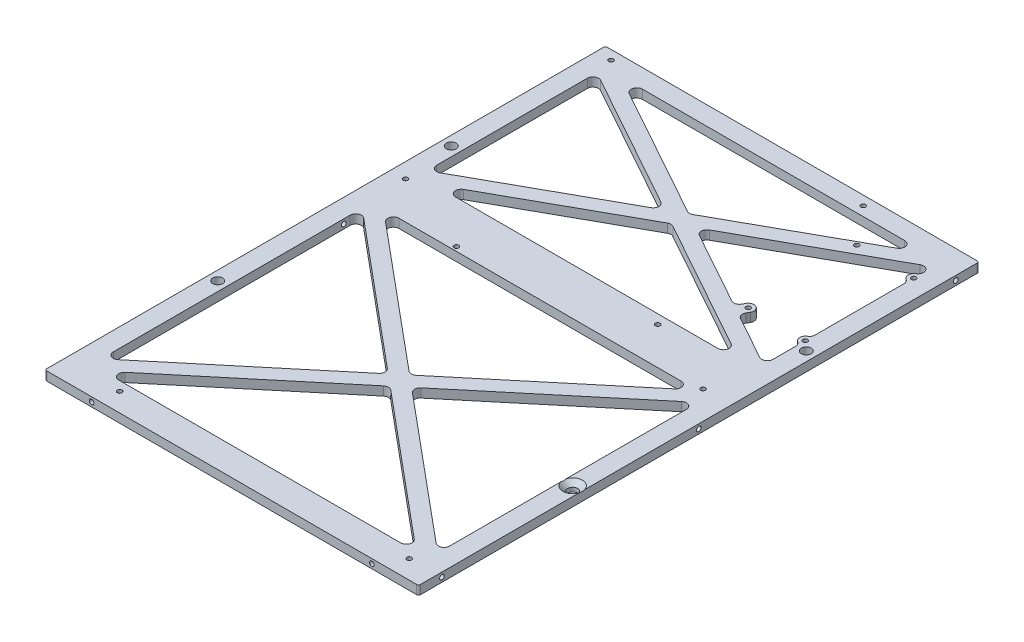
SolidWorks part; units mm, degrees
material "6061 Alloy"
ref_plane "Front Plane" through (0, 0, 0) normal (0, 0, 1) x (1, 0, 0)
ref_plane "Top Plane" through (0, 0, 0) normal (0, 1, 0) x (1, 0, 0)
ref_plane "Right Plane" through (0, 0, 0) normal (1, 0, 0) x (0, 0, -1)
sketch "Sketch1" plane through (0, 0, 0) normal (0, 1, 0) x (1, 0, 0)
  line L1 (-100, -150) -> (100, -150)
  line L2 (-100, -150) -> (-100, 150)
  line L3 (-100, 150) -> (100, 150)
  line L4 (100, -150) -> (100, 150)
  line L5 (-100, -150) -> (100, 150) construction
  line L6 (-100, 150) -> (100, -150) construction
  point P0 (0, 0)
  dimension "D1" = 300
  dimension "D2" = 200
extrude "Boss-Extrude1" add sketch "Sketch1" along normal blind 4.7625
sketch "Sketch10" plane through (0, 4.7625, 0) normal (0, 1, 0) x (1, 0, 0)
  line L0 (-100, -150) -> (100, -150) construction
  line L1 (-70, -140) -> (85, -140) construction
  line L2 (-70, -140) -> (-70, 17.25) construction
  line L3 (-70, 17.25) -> (85, 17.25) construction
  line L4 (85, -140) -> (85, 17.25) construction
  line L5 (-70, -140) -> (85, 17.25) construction
  line L6 (-70, 17.25) -> (85, -140) construction
  line L7 (100, 150) -> (-100, 150) construction
  line L8 (-92, 35) -> (43, 35) construction
  line L14 (-92, 35) -> (-92, 145) construction
  line L15 (100, -150) -> (100, 150) construction
  line L16 (-92, 145) -> (43, 145) construction
  line L17 (-95, -62.5) -> (95, -62.5) construction
  line L18 (-95, -62.5) -> (-95, 62.5) construction
  line L19 (-95, 62.5) -> (95, 62.5) construction
  line L20 (95, -62.5) -> (95, 62.5) construction
  line L21 (-95, -62.5) -> (95, 62.5) construction
  line L22 (-95, 62.5) -> (95, -62.5) construction
  line L23 (43, 35) -> (43, 145) construction
  line L24 (-92, 35) -> (43, 145) construction
  line L25 (-92, 145) -> (43, 35) construction
  line L26 (-100, 150) -> (-100, -150) construction
  line L28 (59.5, 67) -> (90, 67) construction
  line L29 (59.5, 67) -> (59.5, 125) construction
  line L30 (59.5, 125) -> (90, 125) construction
  line L31 (90, 67) -> (90, 125) construction
  line L32 (59.5, 67) -> (90, 125) construction
  line L33 (59.5, 125) -> (90, 67) construction
  point P0 (7.5, -61.375)
  point P7 (-47, 17.25)
  point P9 (-24.5, 90)
  point P14 (74.75, 96)
  point P20 (0, 0)
  dimension "D1" = 155
  dimension "D2" = 157.25
  dimension "D3" = 132
  dimension "D4" = 10
  dimension "D5" = 135
  dimension "D6" = 125
  dimension "D7" = 110
  dimension "D8" = 5
  dimension "D9" = 8
  dimension "D10" = 190
  dimension "D11" = 15
  dimension "D12" = 30.5
  dimension "D13" = 58
  dimension "D14" = 25
  dimension "D15" = 10
sketch "Sketch14" plane through (0, 4.7625, 0) normal (0, 1, 0) x (1, 0, 0)
  line L0 (100, 150) -> (-100, 150) construction
  line L1 (-90, 40) -> (90, 40) construction
  line L2 (-90, 40) -> (-90, 140) construction
  line L3 (-90, 140) -> (90, 140) construction
  line L4 (90, 40) -> (90, 140) construction
  line L5 (-90, 40) -> (90, 140) construction
  line L6 (-90, 140) -> (90, 40) construction
  line L7 (-90, 15) -> (90, 15) construction
  line L8 (-90, 15) -> (-90, -135) construction
  line L9 (-90, -135) -> (90, -135) construction
  line L10 (90, 15) -> (90, -135) construction
  line L11 (-90, 15) -> (90, -135) construction
  line L12 (-90, -135) -> (90, 15) construction
  line L13 (-100, 150) -> (-100, -150) construction
  line L14 (-100, -150) -> (100, -150) construction
  line L15 (-92.5607, 11.9271) -> (87.4393, -138.0729) construction
  line L16 (-87.4393, -138.0729) -> (92.5607, 11.9271) construction
  line L17 (-88.0574, 36.5034) -> (91.9426, 136.5034) construction
  line L18 (-91.9426, 136.5034) -> (88.0574, 36.5034) construction
  line L19 (-87.4393, 18.0729) -> (92.5607, -131.9271) construction
  line L20 (-92.5607, -131.9271) -> (87.4393, 18.0729) construction
  line L21 (-91.9426, 43.4966) -> (88.0574, 143.4966) construction
  line L22 (-88.0574, 143.4966) -> (91.9426, 43.4966) construction
  line L23 (-83.7518, 15) -> (83.7518, 15)
  line L24 (90, 9.7932) -> (90, -129.7932)
  line L25 (83.7518, -135) -> (-83.7518, -135)
  line L26 (-90, -129.7932) -> (-90, 9.7932)
  line L27 (83.7518, 15) -> (0, -54.7932)
  line L28 (0, -54.7932) -> (-83.7518, 15)
  line L29 (-90, 9.7932) -> (-6.2482, -60)
  line L30 (-6.2482, -60) -> (-90, -129.7932)
  line L31 (-83.7518, -135) -> (0, -65.2068)
  line L32 (0, -65.2068) -> (83.7518, -135)
  line L33 (90, -129.7932) -> (6.2482, -60)
  line L34 (6.2482, -60) -> (90, 9.7932)
  line L35 (8.2365, 90) -> (90, 135.4242)
  line L36 (90, 135.4242) -> (90, 44.5758) construction
  line L37 (90, 44.5758) -> (8.2365, 90) construction
  line L38 (81.7635, 140) -> (0, 94.5758)
  line L39 (0, 94.5758) -> (-81.7635, 140)
  line L40 (-81.7635, 140) -> (81.7635, 140)
  line L41 (-90, 135.4242) -> (-8.2365, 90)
  line L42 (-8.2365, 90) -> (-90, 44.5758)
  line L43 (-90, 44.5758) -> (-90, 135.4242)
  line L44 (-81.7635, 40) -> (0, 85.4242)
  line L45 (0, 85.4242) -> (81.7635, 40)
  line L46 (81.7635, 40) -> (-81.7635, 40)
  line L47 (54.5512, 64.2696) -> (56.8775, 68.4569)
  line L48 (62.1225, 65.5431) -> (59.7962, 61.3557)
  line L49 (59.7962, 61.3557) -> (90, 44.5758)
  line L50 (54.5512, 64.2696) -> (8.2365, 90)
  line L51 (90, 64) -> (90, 44.5758)
  line L52 (90, 70) -> (90, 122)
  line L53 (90, 128) -> (90, 135.4242)
  circle A0 centre (90, 125) radius 3 construction
  circle A1 centre (90, 67) radius 3 construction
  circle A2 centre (59.5, 67) radius 3 construction
  arc A3 (56.8775, 68.4569) -> (62.1225, 65.5431) centre (59.5, 67) cw
  arc A4 (90, 70) -> (90, 64) centre (90, 67) ccw
  arc A5 (90, 128) -> (90, 122) centre (90, 125) ccw
  point P0 (0, 90)
  point P5 (0, -60)
  dimension "D9" = 3
  dimension "D10" = 6
  dimension "D11" = 6
  dimension "D1" = 10
  dimension "D2" = 100
  dimension "D3" = 10
  dimension "D4" = 15
  dimension "D5" = 150
  dimension "D6" = 10
  dimension "D7" = 4
  dimension "D8" = 4
extrude "Cut-Extrude1" cut sketch "Sketch14" against normal through all
sketch "Sketch15" plane through (0, 4.7625, 0) normal (0, 1, 0) x (1, 0, 0)
  circle A0 centre (85, -140) radius 3.5
  dimension "D1" = 7
extrude "Boss-Extrude2" add sketch "Sketch15" against normal up to surface (4.7625 mm away) up to face at (70.6401, 0, -83.2953)
hole_wizard "M3x0.5 Tapped Hole3" positions "Sketch11" profile "Sketch12" tap size "M3x0.5" standard "ANSI Metric" end condition through all
sketch "Sketch11" plane through (0, 4.7625, 0) normal (0, 1, 0) x (1, 0, 0)
  point P3 (85, 17.25)
  point P6 (-47, 17.25)
  point P9 (85, -140)
  point P33 (-70, -140)
  point P42 (-92, 145)
  point P45 (-92, 35)
  point P48 (43, 35)
  point P51 (43, 145)
  point P54 (59.5, 67)
  point P57 (90, 67)
  point P60 (90, 125)
  point P63 (59.5, 125)
sketch "Sketch12" plane through (85, 4.7625, -17.25) normal (1, 0, 0) x (0, 0, 1)
  line L0 (0, 0) -> (0, 4.7625)
  line L1 (0, 4.7625) -> (1.25, 4.7625)
  line L2 (1.25, 4.7625) -> (1.25, 0)
  line L5 (1.25, 0) -> (0, 0)
  line L11 (0, -6.35) -> (0, 107.95) construction
  dimension "Thru Tap Drill Dia." = 2.5
  dimension "Thru Tap Drill Depth" = 4.7625
cosmetic thread "Hole Thread7" parameters "D2"=3
cosmetic thread "Hole Thread9" parameters "D2"=3
cosmetic thread "Hole Thread32" parameters "D2"=3
cosmetic thread "Hole Thread33" parameters "D2"=3
cosmetic thread "Hole Thread38" parameters "D2"=3
cosmetic thread "Hole Thread39" parameters "D2"=3
cosmetic thread "Hole Thread40" parameters "D2"=3
cosmetic thread "Hole Thread41" parameters "D2"=3
cosmetic thread "Hole Thread42" parameters "D2"=3
cosmetic thread "Hole Thread43" parameters "D2"=3
cosmetic thread "Hole Thread44" parameters "D2"=3
cosmetic thread "Hole Thread45" parameters "D2"=3
hole_wizard "M5 Clearance Hole1" positions "Sketch26" profile "Sketch27" hole size "M5" standard "ANSI Metric" end condition through all
sketch "Sketch26" plane through (0, 4.7625, 0) normal (0, 1, 0) x (1, 0, 0)
  point P0 (-95, 62.5)
  point P3 (-95, -62.5)
  point P6 (95, -62.5)
  point P9 (95, 62.5)
sketch "Sketch27" plane through (-95, 4.7625, -62.5) normal (1, 0, 0) x (0, 0, 1)
  line L0 (0, 0) -> (0, 4.7625)
  line L1 (0, 4.7625) -> (2.65, 4.7625)
  line L2 (2.65, 4.7625) -> (2.65, 0)
  line L5 (2.65, 0) -> (0, 0)
  line L11 (0, -6.35) -> (0, 107.95) construction
  dimension "Thru Hole Dia." = 5.3
  dimension "Thru Hole Depth" = 4.7625
hole_wizard "CSK for M5 Flat Head Machine Screw1" positions "Sketch28" profile "Sketch29" countersink size "M5" standard "ANSI Metric" end condition through all
sketch "Sketch28" plane through (0, 4.7625, 0) normal (0, 1, 0) x (1, 0, 0)
  point P0 (95, -62.5)
sketch "Sketch29" plane through (95, 4.7625, 62.5) normal (1, 0, 0) x (0, 0, 1)
  line L0 (0, 0) -> (0, 4.7625)
  line L1 (0, 4.7625) -> (2.65, 4.7625)
  line L2 (2.65, 4.7625) -> (2.65, 2.55)
  line L3 (2.65, 2.55) -> (5.2, 0)
  line L5 (5.2, 0) -> (0, 0)
  line L6 (-2.65, 2.55) -> (-5.2, 0) construction
  line L11 (0, -6.35) -> (0, 107.95) construction
  dimension "Thru Hole Dia." = 5.3
  dimension "Thru Hole Depth" = 4.7625
  dimension "Near C'Sink Dia." = 10.4
  dimension "Near C'Sink Angle" = 90
fillet "Fillet2" radius 3 30 edges at (81.7635, 2.3813, -140) (-81.7635, 2.3813, -140) (0, 2.3813, -94.5758) (0, 2.3813, -85.4242) (81.7635, 2.3813, -40) (-81.7635, 2.3813, -40) (-90, 2.3813, -135.4242) (-8.2365, 2.3813, -90) (-90, 2.3813, -44.5758) (90, 2.3813, -9.7932) (90, 2.3813, 129.7932) (83.7518, 2.3813, 135) (-83.7518, 2.3813, 135) (-90, 2.3813, 129.7932) (-6.2482, 2.3813, 60) (6.2482, 2.3813, 60) (0, 2.3813, 65.2068) (-90, 2.3813, -9.7932) (83.7518, 2.3813, -15) (0, 2.3813, 54.7932) (-83.7518, 2.3813, -15) (90, 2.3813, -135.4242) (90, 2.3813, -128) (90, 2.3813, -122) (90, 2.3813, -70) (90, 2.3813, -64) (90, 2.3813, -44.5758) (59.7962, 2.3813, -61.3557) (54.5512, 2.3813, -64.2696) (8.2365, 2.3813, -90)
sketch "Sketch17" plane through (0, 0, 150) normal (0, 0, 1) x (1, 0, 0)
  line L0 (-75, 2.3813) -> (75, 2.3813) construction
  line L1 (-100, 4.7625) -> (-100, 0) construction
  point P3 (0, 2.3813)
  point P7 (-100, 2.3813)
  dimension "D1" = 150
hole_wizard "M3x0.5 Tapped Hole4" positions "Sketch20" profile "Sketch22" tap size "M3x0.5" standard "ANSI Metric"
sketch "Sketch20" plane through (0, 0, 150) normal (0, 0, 1) x (1, 0, 0)
  point P0 (-75, 2.3813)
  point P3 (75, 2.3813)
sketch "Sketch22" plane through (-75, 2.3813, 150) normal (1, 0, 0) x (0, -1, 0)
  line L0 (0, 0) -> (0, 10.7511)
  line L1 (0, 10.7511) -> (1.25, 10)
  line L2 (1.25, 10) -> (1.25, 0)
  line L5 (1.25, 0) -> (0, 0)
  line L10 (0, 10.7511) -> (-1.25, 10) construction
  line L11 (0, -6.35) -> (0, 107.95) construction
  dimension "Tap Drill Dia." = 2.5
  dimension "Tap Drill Depth" = 10
  dimension "Drill Angle" = 118
cosmetic thread "Hole Thread22" parameters "D1"=4.76, "D2"=3
cosmetic thread "Hole Thread23" parameters "D1"=4.76, "D2"=3
mirror "Mirror1" about plane through (0, 0, 0) normal (0, 0, 1) of "M3x0.5 Tapped Hole4"
cosmetic thread "Hole Thread28" parameters "D1"=4.76, "D2"=3
cosmetic thread "Hole Thread29" parameters "D1"=4.76, "D2"=3
sketch "Sketch23" plane through (-100, 0, 0) normal (-1, 0, 0) x (0, 0, 1)
  line L0 (-137.5, 2.3813) -> (137.5, 2.3813) construction
  line L1 (-150, 4.7625) -> (-150, 0) construction
  point P3 (0, 2.3813)
  point P6 (-150, 2.3813)
  dimension "D1" = 275
hole_wizard "M3x0.5 Tapped Hole5" positions "Sketch24" profile "Sketch25" tap size "M3x0.5" standard "ANSI Metric"
sketch "Sketch24" plane through (-100, 0, 0) normal (-1, 0, 0) x (0, 0, 1)
  point P0 (-137.5, 2.3813)
  point P3 (0, 2.3813)
  point P6 (137.5, 2.3813)
sketch "Sketch25" plane through (-100, 2.3813, -137.5) normal (0, 1, 0) x (0, 0, 1)
  line L0 (0, 0) -> (0, 10.7511)
  line L1 (0, 10.7511) -> (1.25, 10)
  line L2 (1.25, 10) -> (1.25, 0)
  line L5 (1.25, 0) -> (0, 0)
  line L10 (0, 10.7511) -> (-1.25, 10) construction
  line L11 (0, -6.35) -> (0, 107.95) construction
  dimension "Tap Drill Dia." = 2.5
  dimension "Tap Drill Depth" = 10
  dimension "Drill Angle" = 118
cosmetic thread "Hole Thread25" parameters "D1"=5, "D2"=3
cosmetic thread "Hole Thread34" parameters "D1"=5, "D2"=3
cosmetic thread "Hole Thread35" parameters "D1"=5, "D2"=3
mirror "Mirror2" about plane through (0, 0, 0) normal (1, 0, 0) of "M3x0.5 Tapped Hole5"
cosmetic thread "Hole Thread30" parameters "D1"=5, "D2"=3
cosmetic thread "Hole Thread36" parameters "D1"=5, "D2"=3
cosmetic thread "Hole Thread37" parameters "D1"=5, "D2"=3
fillet "Fillet1" radius 1 4 edges at (100, 2.3813, 150) (-100, 2.3813, 150) (-100, 2.3813, -150) (100, 2.3813, -150)
